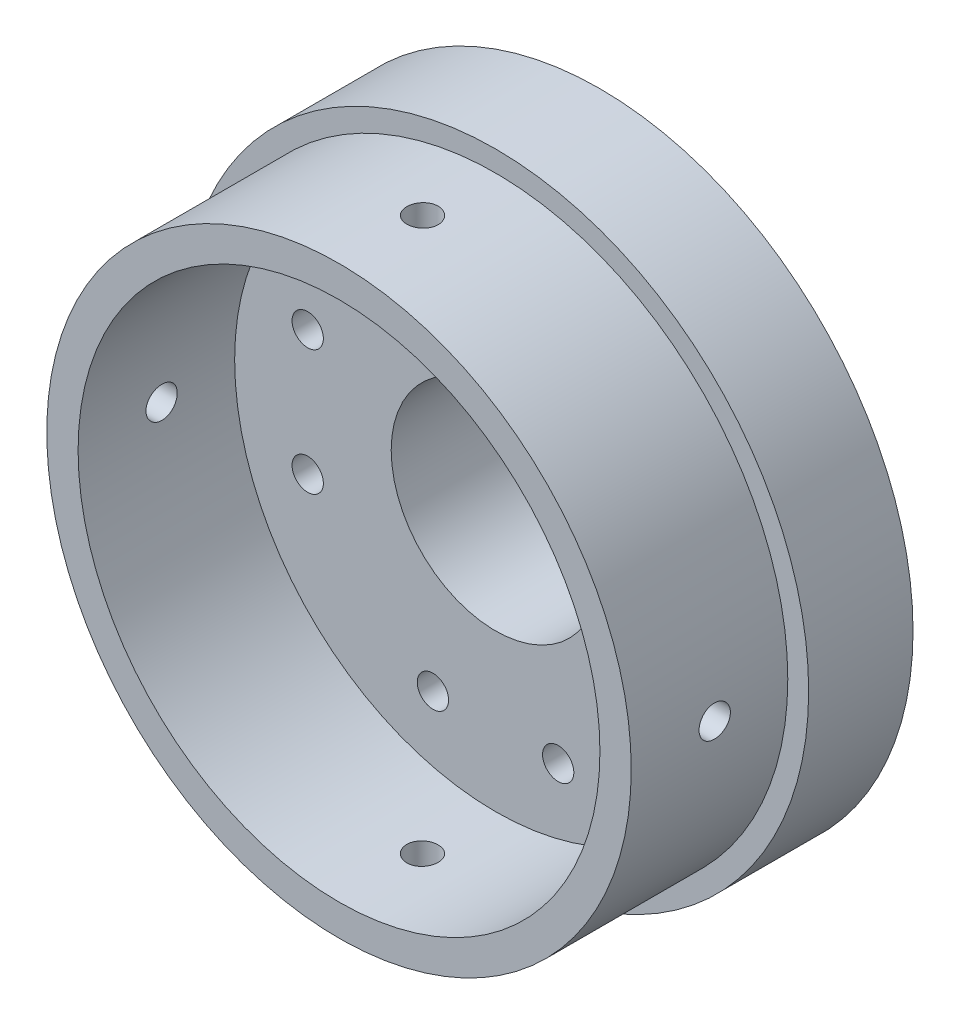
SolidWorks part; units mm, degrees
ref_plane "정면" through (0, 0, 0) normal (0, 0, 1) x (1, 0, 0)
ref_plane "윗면" through (0, 0, 0) normal (0, 1, 0) x (1, 0, 0)
ref_plane "우측면" through (0, 0, 0) normal (1, 0, 0) x (0, 0, -1)
sketch "스케치1" plane through (0, 0, 0) normal (0, 0, 1) x (1, 0, 0)
  circle A0 centre (0, 0) radius 30
extrude "보스-돌출1" add sketch "스케치1" along normal blind 10
sketch "스케치2" plane through (0, 0, 10) normal (0, 0, 1) x (1, 0, 0)
  circle A0 centre (0, 0) radius 28
  circle A1 centre (0, 0) radius 25
extrude "보스-돌출2" add sketch "스케치2" along normal blind 15
sketch "스케치3" plane through (0, 30, 0) normal (0, 1, 0) x (1, 0, 0)
  circle A0 centre (0, -17) radius 1.5
extrude "컷-돌출1" cut sketch "스케치3" against normal through all both and the other way through all
sketch "스케치4" plane through (-27, 0, 0) normal (-1, 0, 0) x (0, 0, 1)
  circle A0 centre (17, 0) radius 1.5
extrude "컷-돌출2" cut sketch "스케치4" against normal through all both and the other way through all
sketch "스케치5" plane through (0, 0, 0) normal (0, 0, -1) x (-1, 0, 0)
  circle A0 centre (-6, -18) radius 1.5
  circle A1 centre (6, -18) radius 1.5
  circle A2 centre (18, -6) radius 1.5
  circle A3 centre (18, 6) radius 1.5
  circle A4 centre (6, 18) radius 1.5
  circle A5 centre (-6, 18) radius 1.5
  circle A6 centre (-18, 6) radius 1.5
  circle A7 centre (-18, -6) radius 1.5
  dimension "D1" = 3
  dimension "D2" = 3
  dimension "D3" = 3
  dimension "D4" = 3
  dimension "D5" = 3
  dimension "D6" = 3
  dimension "D7" = 3
  dimension "D8" = 3
extrude "컷-돌출3" cut sketch "스케치5" against normal blind 15
sketch "스케치6" plane through (0, 0, 0) normal (0, 0, -1) x (-1, 0, 0)
  circle A0 centre (0, 0) radius 10
  dimension "D1" = 20
extrude "컷-돌출4" cut sketch "스케치6" against normal blind 10
